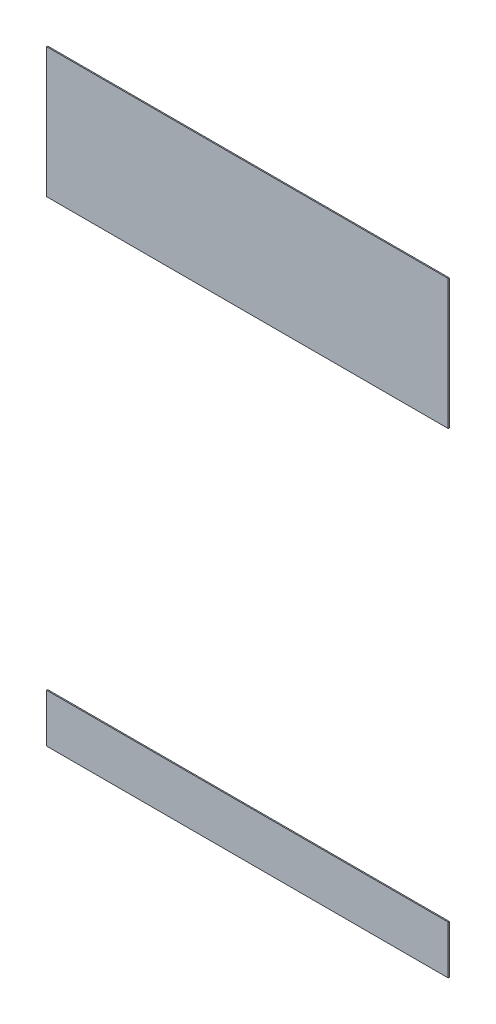
SolidWorks part; units mm, degrees
ref_plane "前视基准面" through (0, 0, 0) normal (0, 0, 1) x (1, 0, 0)
ref_plane "上视基准面" through (0, 0, 0) normal (0, 1, 0) x (1, 0, 0)
ref_plane "右视基准面" through (0, 0, 0) normal (1, 0, 0) x (0, 0, -1)
sketch "草图4" plane through (0, 0, 0) normal (0, 0, 1) x (1, 0, 0)
  line L1 (-370, 565) -> (-10, 565)
  line L2 (-370, 565) -> (-370, 448.5)
  line L3 (-370, 448.5) -> (-10, 448.5)
  line L4 (-10, 565) -> (-10, 448.5)
extrude "凸台-拉伸2" add sketch "草图4" against normal blind 1
sketch "草图5" plane through (0, 0, 0) normal (0, 0, 1) x (1, 0, 0)
  line L2 (-10, 22) -> (-370, 22)
  line L3 (-10, 22) -> (-10, 65.3945)
  line L4 (-10, 65.3945) -> (-370, 65.3945)
  line L5 (-370, 22) -> (-370, 65.3945)
extrude "凸台-拉伸3" add sketch "草图5" against normal blind 1 separate body
sketch "草图8" plane through (0, 0, 0) normal (0, 0, 1) x (1, 0, 0)
  line L0 (183.0383, 80.6223) -> (72.3717, 80.6223) construction
sketch "草图9" plane through (0, 0, 0) normal (0, 0, 1) x (1, 0, 0)
  line L0 (-24.1667, -656.0734) -> (-120.8333, -656.0734) construction
